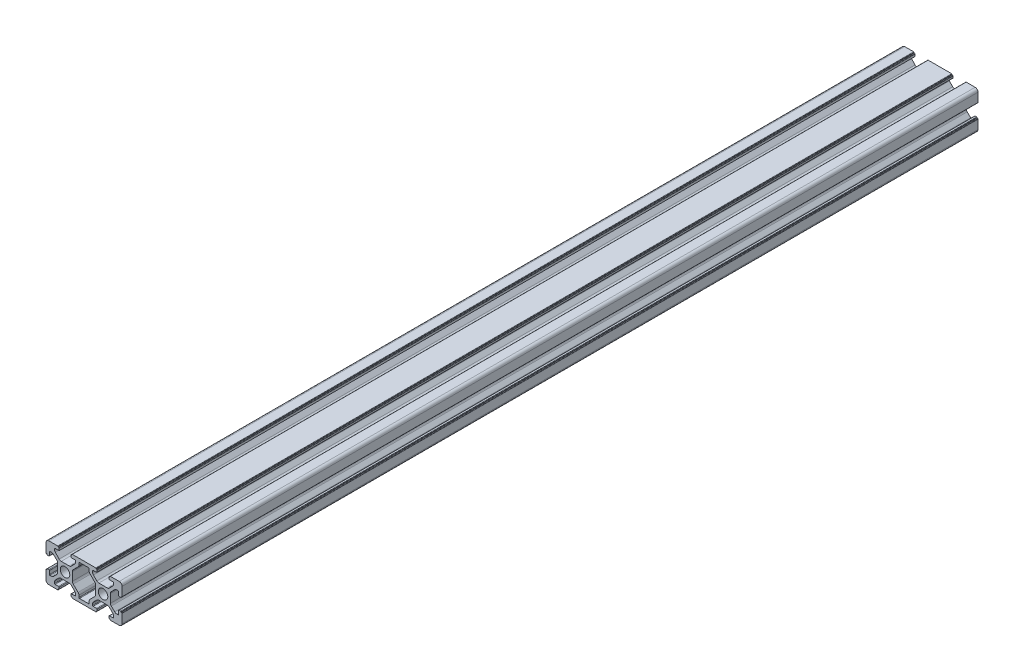
SolidWorks part; units mm, degrees
material "6063-T5"
ref_plane "Front Plane" through (0, 0, 0) normal (0, 0, 1) x (1, 0, 0)
ref_plane "Top Plane" through (0, 0, 0) normal (0, 1, 0) x (1, 0, 0)
ref_plane "Right Plane" through (0, 0, 0) normal (1, 0, 0) x (0, 0, -1)
sketch "Sketch1" plane through (0, 0, 0) normal (0, 0, 1) x (1, 0, 0)
  line L0 (1.5, 0) -> (6.2, 0)
  line L1 (40, 1.5) -> (40, 6.2)
  line L2 (38.5, 20) -> (33.8, 20)
  line L3 (0, 18.5) -> (0, 13.8)
  line L4 (17.6, 1.8) -> (22.4, 1.8)
  line L5 (32.218, 13.9) -> (27.782, 13.9)
  line L6 (26.1, 12.218) -> (26.1, 7.782)
  line L7 (17.6, 18.2) -> (22.4, 18.2)
  line L8 (12.218, 13.9) -> (7.9864, 13.9)
  line L9 (6.1, 12.218) -> (6.1, 7.782)
  line L10 (7.782, 6.1) -> (12.218, 6.1)
  line L11 (13.9, 7.782) -> (13.9, 12.218)
  line L12 (27.782, 6.1) -> (32.218, 6.1)
  line L13 (33.9, 7.782) -> (33.9, 12.218)
  line L14 (26.7213, 14.3393) -> (24.9393, 16.1213)
  line L15 (33.2787, 14.3393) -> (35.0607, 16.1213)
  line L16 (34.3393, 13.2787) -> (36.1213, 15.0607)
  line L17 (25.6607, 6.7213) -> (23.1393, 4.2)
  line L18 (15.2, 1.8) -> (13.4, 1.8)
  line L19 (26.7213, 5.6607) -> (24.9393, 3.8787)
  line L20 (24.8, 1.8) -> (26.6, 1.8)
  line L21 (15.3, 18.2) -> (13.1, 18.2)
  line L22 (13.2787, 14.3393) -> (15.1607, 16.2213)
  line L23 (14.3393, 13.2787) -> (16.8607, 15.8)
  line L24 (5.6607, 6.7213) -> (3.8787, 4.9393)
  line L25 (6.7213, 5.6607) -> (4.9393, 3.8787)
  line L26 (6.897, 14.3689) -> (4.9106, 16.4674)
  line L27 (5.6607, 13.2787) -> (3.8787, 15.0607)
  line L28 (14.3393, 6.7213) -> (16.8607, 4.2)
  line L29 (13.2787, 5.6607) -> (15.0607, 3.8787)
  line L30 (24.8, 18.2) -> (26.6, 18.2)
  line L31 (25.6607, 13.2787) -> (23.1393, 15.8)
  line L32 (34.3393, 6.7213) -> (36.1213, 4.9393)
  line L33 (33.2787, 5.6607) -> (35.0607, 3.8787)
  line L34 (1.8, 15.2) -> (1.8, 13.4)
  line L35 (24.5, 2.1) -> (24.5, 2.818)
  line L36 (4.5, 2.1) -> (4.5, 2.818)
  line L37 (2.818, 4.5) -> (2.1, 4.5)
  line L38 (4.5, 17.9) -> (4.5, 17.4986)
  line L39 (2.818, 15.5) -> (2.1, 15.5)
  line L40 (15.6, 17.9) -> (15.6, 17.282)
  line L41 (15.5, 2.818) -> (15.5, 2.1)
  line L42 (38.2, 15.2) -> (38.2, 13.4)
  line L43 (35.5, 2.818) -> (35.5, 2.1)
  line L44 (37.182, 4.5) -> (37.9, 4.5)
  line L45 (35.5, 17.182) -> (35.5, 17.9)
  line L46 (37.182, 15.5) -> (37.9, 15.5)
  line L47 (17.3, 2.1) -> (17.3, 3.1393)
  line L48 (22.7, 2.1) -> (22.7, 3.1393)
  line L49 (17.3, 17.9) -> (17.3, 16.8607)
  line L50 (22.7, 17.9) -> (22.7, 16.8607)
  line L51 (24.5, 17.9) -> (24.5, 17.182)
  line L52 (6.9, 19.3) -> (6.9, 18.2)
  line L53 (13.1, 19.3) -> (13.1, 18.2)
  line L54 (6.9, 1.5) -> (6.9, 0.7)
  line L55 (13.1, 1.5) -> (13.1, 0.7)
  line L56 (13.8, 0) -> (26.2, 0)
  line L57 (6.6, 1.8) -> (4.8, 1.8)
  line L58 (6.9, 18.2) -> (4.8, 18.2)
  line L59 (6.2, 20) -> (1.5, 20)
  line L60 (39.3, 6.9) -> (38.5, 6.9)
  line L61 (39.3, 13.1) -> (38.5, 13.1)
  line L62 (1.5, 13.1) -> (0.7, 13.1)
  line L63 (1.5, 6.9) -> (0.7, 6.9)
  line L64 (0, 6.2) -> (0, 1.5)
  line L65 (1.8, 6.6) -> (1.8, 4.8)
  line L66 (38.2, 6.6) -> (38.2, 4.8)
  line L67 (40, 13.8) -> (40, 18.5)
  line L68 (33.1, 19.3) -> (33.1, 18.5)
  line L69 (26.9, 19.3) -> (26.9, 18.5)
  line L70 (26.9, 1.5) -> (26.9, 0.7)
  line L71 (33.1, 1.5) -> (33.1, 0.7)
  line L72 (33.8, 0) -> (38.5, 0)
  line L73 (33.4, 1.8) -> (35.2, 1.8)
  line L74 (26.2, 20) -> (13.8, 20)
  line L75 (33.4, 18.2) -> (35.2, 18.2)
  line L76 (6.7, 0.5) -> (6.6, 0.5)
  line L77 (6.4, 0.3) -> (6.4, 0.2)
  line L78 (13.3, 0.5) -> (13.4, 0.5)
  line L79 (13.6, 0.3) -> (13.6, 0.2)
  line L80 (26.7, 0.5) -> (26.6, 0.5)
  line L81 (26.4, 0.3) -> (26.4, 0.2)
  line L82 (33.3, 0.5) -> (33.4, 0.5)
  line L83 (33.6, 0.3) -> (33.6, 0.2)
  line L85 (6.4, 19.8) -> (6.4, 19.7)
  line L86 (6.6, 19.5) -> (6.7, 19.5)
  line L87 (13.6, 19.8) -> (13.6, 19.7)
  line L88 (13.4, 19.5) -> (13.3, 19.5)
  line L89 (26.4, 19.8) -> (26.4, 19.7)
  line L90 (26.6, 19.5) -> (26.7, 19.5)
  line L91 (33.6, 19.8) -> (33.6, 19.7)
  line L92 (33.4, 19.5) -> (33.3, 19.5)
  line L93 (0.5, 13.3) -> (0.5, 13.4)
  line L94 (0.3, 13.6) -> (0.2, 13.6)
  line L95 (0.5, 6.7) -> (0.5, 6.6)
  line L96 (0.3, 6.4) -> (0.2, 6.4)
  line L97 (39.5, 13.3) -> (39.5, 13.4)
  line L98 (39.7, 13.6) -> (39.8, 13.6)
  line L99 (39.5, 6.7) -> (39.5, 6.6)
  line L100 (39.7, 6.4) -> (39.8, 6.4)
  circle A0 centre (10, 10) radius 2.5
  circle A1 centre (30, 10) radius 2.5
  arc A2 (38.5, 0) -> (40, 1.5) centre (38.5, 1.5) ccw
  arc A3 (40, 18.5) -> (38.5, 20) centre (38.5, 18.5) ccw
  arc A4 (1.5, 0) -> (0, 1.5) centre (1.5, 1.5) cw
  arc A5 (1.5, 20) -> (0, 18.5) centre (1.5, 18.5) ccw
  arc A6 (26.7213, 5.6607) -> (27.782, 6.1) centre (27.782, 4.6) cw
  arc A7 (32.218, 6.1) -> (33.2787, 5.6607) centre (32.218, 4.6) cw
  arc A8 (33.9, 7.782) -> (34.3393, 6.7213) centre (35.4, 7.782) ccw
  arc A9 (33.2787, 14.3393) -> (32.218, 13.9) centre (32.218, 15.4) cw
  arc A10 (14.3393, 6.7213) -> (13.9, 7.782) centre (15.4, 7.782) cw
  arc A11 (14.3393, 13.2787) -> (13.9, 12.218) centre (15.4, 12.218) ccw
  arc A12 (25.6607, 6.7213) -> (26.1, 7.782) centre (24.6, 7.782) ccw
  arc A13 (26.1, 12.218) -> (25.6607, 13.2787) centre (24.6, 12.218) ccw
  arc A14 (27.782, 13.9) -> (26.7213, 14.3393) centre (27.782, 15.4) cw
  arc A15 (5.6607, 13.2787) -> (6.1, 12.218) centre (4.6, 12.218) cw
  arc A16 (5.6607, 6.7213) -> (6.1, 7.782) centre (4.6, 7.782) ccw
  arc A17 (13.2787, 5.6607) -> (12.218, 6.1) centre (12.218, 4.6) ccw
  arc A18 (6.7213, 5.6607) -> (7.782, 6.1) centre (7.782, 4.6) cw
  arc A19 (13.2787, 14.3393) -> (12.218, 13.9) centre (12.218, 15.4) cw
  arc A20 (6.897, 14.3689) -> (7.9864, 13.9) centre (7.9864, 15.4) ccw
  arc A21 (36.1213, 4.9393) -> (37.182, 4.5) centre (37.182, 6) ccw
  arc A22 (36.1213, 15.0607) -> (37.182, 15.5) centre (37.182, 14) cw
  arc A23 (35.0607, 16.1213) -> (35.5, 17.182) centre (34, 17.182) ccw
  arc A24 (24.5, 17.182) -> (24.9393, 16.1213) centre (26, 17.182) ccw
  arc A25 (22.7, 16.8607) -> (23.1393, 15.8) centre (24.2, 16.8607) ccw
  arc A26 (17.3, 16.8607) -> (16.8607, 15.8) centre (15.8, 16.8607) cw
  arc A27 (4.9106, 16.4674) -> (4.5, 17.4986) centre (6, 17.4986) cw
  arc A28 (15.6, 17.282) -> (15.1607, 16.2213) centre (14.1, 17.282) cw
  arc A29 (3.8787, 15.0607) -> (2.818, 15.5) centre (2.818, 14) ccw
  arc A30 (3.8787, 4.9393) -> (2.818, 4.5) centre (2.818, 6) cw
  arc A31 (4.9393, 3.8787) -> (4.5, 2.818) centre (6, 2.818) ccw
  arc A32 (35.0607, 3.8787) -> (35.5, 2.818) centre (34, 2.818) cw
  arc A33 (24.9393, 3.8787) -> (24.5, 2.818) centre (26, 2.818) ccw
  arc A34 (22.7, 3.1393) -> (23.1393, 4.2) centre (24.2, 3.1393) cw
  arc A35 (17.3, 3.1393) -> (16.8607, 4.2) centre (15.8, 3.1393) ccw
  arc A36 (15.5, 2.818) -> (15.0607, 3.8787) centre (14, 2.818) ccw
  arc A37 (1.8, 6.6) -> (1.5, 6.9) centre (1.5, 6.6) ccw
  arc A38 (1.8, 13.4) -> (1.5, 13.1) centre (1.5, 13.4) cw
  arc A39 (17.6, 18.2) -> (17.3, 17.9) centre (17.6, 17.9) ccw
  arc A40 (22.4, 1.8) -> (22.7, 2.1) centre (22.4, 2.1) ccw
  arc A41 (17.6, 1.8) -> (17.3, 2.1) centre (17.6, 2.1) cw
  arc A42 (15.2, 1.8) -> (15.5, 2.1) centre (15.2, 2.1) ccw
  arc A43 (6.6, 1.8) -> (6.9, 1.5) centre (6.6, 1.5) cw
  arc A44 (13.4, 1.8) -> (13.1, 1.5) centre (13.4, 1.5) ccw
  arc A45 (24.8, 1.8) -> (24.5, 2.1) centre (24.8, 2.1) cw
  arc A46 (35.2, 1.8) -> (35.5, 2.1) centre (35.2, 2.1) ccw
  arc A47 (26.6, 1.8) -> (26.9, 1.5) centre (26.6, 1.5) cw
  arc A48 (33.4, 1.8) -> (33.1, 1.5) centre (33.4, 1.5) ccw
  arc A49 (26.9, 18.5) -> (26.6, 18.2) centre (26.6, 18.5) cw
  arc A50 (33.1, 18.5) -> (33.4, 18.2) centre (33.4, 18.5) ccw
  arc A51 (37.9, 4.5) -> (38.2, 4.8) centre (37.9, 4.8) ccw
  arc A52 (38.5, 13.1) -> (38.2, 13.4) centre (38.5, 13.4) cw
  arc A53 (38.5, 6.9) -> (38.2, 6.6) centre (38.5, 6.6) ccw
  arc A54 (38.2, 15.2) -> (37.9, 15.5) centre (37.9, 15.2) ccw
  arc A55 (35.2, 18.2) -> (35.5, 17.9) centre (35.2, 17.9) cw
  arc A56 (24.8, 18.2) -> (24.5, 17.9) centre (24.8, 17.9) ccw
  arc A57 (22.4, 18.2) -> (22.7, 17.9) centre (22.4, 17.9) cw
  arc A58 (15.3, 18.2) -> (15.6, 17.9) centre (15.3, 17.9) cw
  arc A59 (4.5, 17.9) -> (4.8, 18.2) centre (4.8, 17.9) cw
  arc A60 (1.8, 15.2) -> (2.1, 15.5) centre (2.1, 15.2) cw
  arc A61 (1.8, 4.8) -> (2.1, 4.5) centre (2.1, 4.8) ccw
  arc A62 (4.5, 2.1) -> (4.8, 1.8) centre (4.8, 2.1) ccw
  arc A63 (34.3393, 13.2787) -> (33.9, 12.218) centre (35.4, 12.218) ccw
  arc A64 (6.4, 0.2) -> (6.2, 0) centre (6.2, 0.2) cw
  arc A65 (6.6, 0.5) -> (6.4, 0.3) centre (6.6, 0.3) ccw
  arc A66 (6.7, 0.5) -> (6.9, 0.7) centre (6.7, 0.7) ccw
  arc A67 (13.6, 0.2) -> (13.8, 0) centre (13.8, 0.2) ccw
  arc A68 (13.4, 0.5) -> (13.6, 0.3) centre (13.4, 0.3) cw
  arc A69 (13.3, 0.5) -> (13.1, 0.7) centre (13.3, 0.7) cw
  arc A70 (26.4, 0.2) -> (26.2, 0) centre (26.2, 0.2) cw
  arc A71 (26.6, 0.5) -> (26.4, 0.3) centre (26.6, 0.3) ccw
  arc A72 (26.7, 0.5) -> (26.9, 0.7) centre (26.7, 0.7) ccw
  arc A73 (33.6, 0.2) -> (33.8, 0) centre (33.8, 0.2) ccw
  arc A74 (33.4, 0.5) -> (33.6, 0.3) centre (33.4, 0.3) cw
  arc A75 (33.3, 0.5) -> (33.1, 0.7) centre (33.3, 0.7) cw
  arc A76 (39.8, 6.4) -> (40, 6.2) centre (39.8, 6.2) cw
  arc A77 (39.5, 6.6) -> (39.7, 6.4) centre (39.7, 6.6) ccw
  arc A78 (39.5, 6.7) -> (39.3, 6.9) centre (39.3, 6.7) ccw
  arc A79 (39.5, 13.3) -> (39.3, 13.1) centre (39.3, 13.3) cw
  arc A80 (39.5, 13.4) -> (39.7, 13.6) centre (39.7, 13.4) cw
  arc A81 (39.8, 13.6) -> (40, 13.8) centre (39.8, 13.8) ccw
  arc A82 (33.3, 19.5) -> (33.1, 19.3) centre (33.3, 19.3) ccw
  arc A83 (33.6, 19.7) -> (33.4, 19.5) centre (33.4, 19.7) cw
  arc A84 (33.6, 19.8) -> (33.8, 20) centre (33.8, 19.8) cw
  arc A85 (26.7, 19.5) -> (26.9, 19.3) centre (26.7, 19.3) cw
  arc A86 (26.4, 19.7) -> (26.6, 19.5) centre (26.6, 19.7) ccw
  arc A87 (26.4, 19.8) -> (26.2, 20) centre (26.2, 19.8) ccw
  arc A88 (0.2, 6.4) -> (0, 6.2) centre (0.2, 6.2) ccw
  arc A89 (0.5, 6.6) -> (0.3, 6.4) centre (0.3, 6.6) cw
  arc A90 (0.5, 6.7) -> (0.7, 6.9) centre (0.7, 6.7) cw
  arc A91 (13.3, 19.5) -> (13.1, 19.3) centre (13.3, 19.3) ccw
  arc A92 (13.6, 19.7) -> (13.4, 19.5) centre (13.4, 19.7) cw
  arc A93 (13.6, 19.8) -> (13.8, 20) centre (13.8, 19.8) cw
  arc A94 (6.2, 20) -> (6.4, 19.8) centre (6.2, 19.8) cw
  arc A95 (6.7, 19.5) -> (6.9, 19.3) centre (6.7, 19.3) cw
  arc A96 (6.4, 19.7) -> (6.6, 19.5) centre (6.6, 19.7) ccw
  arc A97 (0.5, 13.3) -> (0.7, 13.1) centre (0.7, 13.3) ccw
  arc A98 (0.2, 13.6) -> (0, 13.8) centre (0.2, 13.8) cw
  arc A99 (0.5, 13.4) -> (0.3, 13.6) centre (0.3, 13.4) ccw
  point P87 (0, 0)
  point P178 (1.8, 6.9)
  point P181 (1.8, 13.1)
  point P186 (22.7, 1.8)
  point P193 (6.9, 1.8)
  point P204 (33.1, 1.8)
  point P209 (33.1, 18.2)
  point P216 (38.2, 6.9)
  point P243 (6.9, 0.5)
  point P248 (13.6, 0.5)
  point P257 (26.9, 0.5)
extrude "Boss-Extrude2" add sketch "Sketch1" along normal blind 450 contours A57 L7 A39 L49 A26 L23 A11 L11 A10 L28 A35 L47 A41 L4 A40 L48 A34 L17 A12 L6 A13 L31 A25 L50 | A0 | A1 | L59 A5 L3 A98 L94 A99 L93 A97 L62 A38 L34 A60 L39 A29 L27 A15 L9 A16 L24 A30 L37 A61 L65 A37 L63 A90 L95 A89 L96 A88 L64 A4 L0 A64 L77 A65 L76 A66 L54 A43 L57 A62 L36 A31 L25 A18 L10 A17 L29 A36 L41 A42 L18 A44 L55 A69 L78 A68 L79 A67 L56 A70 L81 A71 L80 A72 L70 A47 L20 A45 L35 A33 L19 A6 L12 A7 L33 A32 L43 A46 L73 A48 L71 A75 L82 A74 L83 A73 L72 A2 L1 A76 L100 A77 L99 A78 L60 A53 L66 A51 L44 A21 L32 A8 L13 A63 L16 A22 L46 A54 L42 A52 L61 A79 L97 A80 L98 A81 L67 A3 L2 A84 L91 A83 L92 A82 L68 A50 L75 A55 L45 A23 L15 A9 L5 A14 L14 A24 L51 A56 L30 A49 L69 A85 L90 A86 L89 A87 L74 A93 L87 A92 L88 A91 L53 L21 A58 L40 A28 L22 A19 L8 A20 L26 A27 L38 A59 L58 L52 A95 L86 A96 L85 A94
